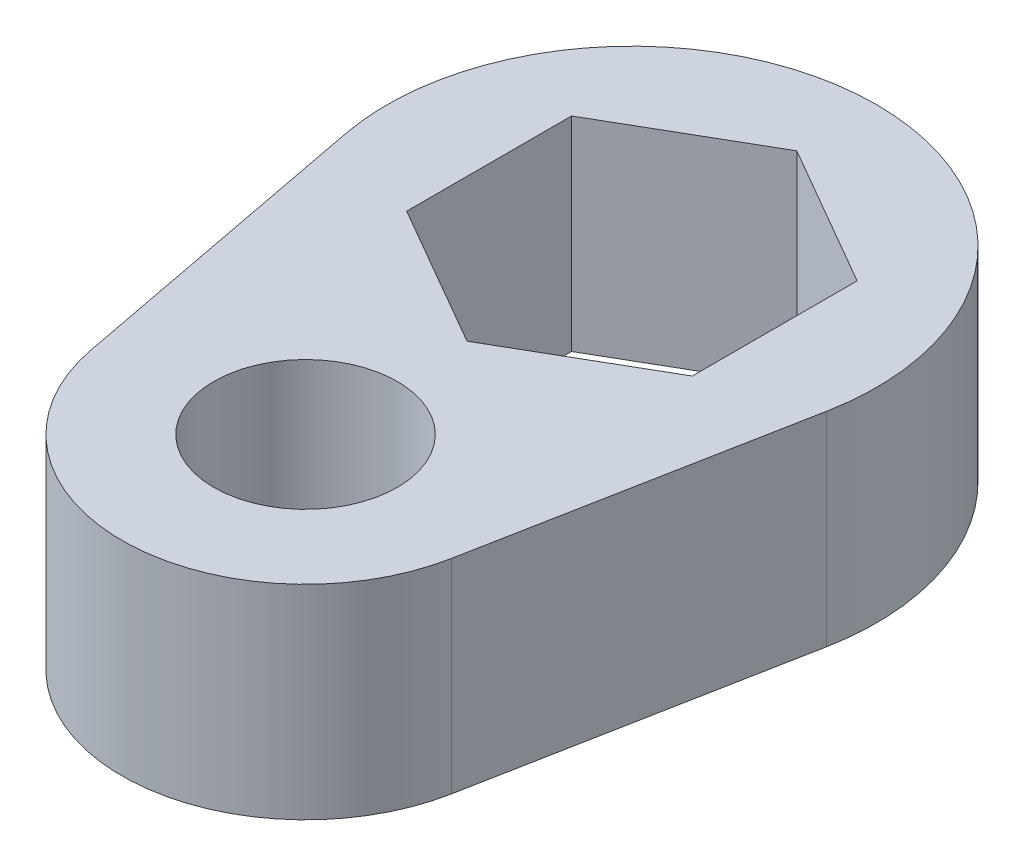
SolidWorks part; units mm, degrees
material "Printed PLA"
ref_plane "Front Plane" through (0, 0, 0) normal (0, 0, 1) x (1, 0, 0)
ref_plane "Top Plane" through (0, 0, 0) normal (0, 1, 0) x (1, 0, 0)
ref_plane "Right Plane" through (0, 0, 0) normal (1, 0, 0) x (0, 0, -1)
sketch "Sketch1" plane through (0, 0, 0) normal (0, 1, 0) x (1, 0, 0)
  line L0 (0, -8) -> (0, 0) construction
  line L1 (0, 4.0415) -> (-3.5, 2.0207)
  line L2 (-3.5, 2.0207) -> (-3.5, -2.0207)
  line L3 (-3.5, -2.0207) -> (0, -4.0415)
  line L4 (0, -4.0415) -> (3.5, -2.0207)
  line L5 (3.5, -2.0207) -> (3.5, 2.0207)
  line L6 (3.5, 2.0207) -> (0, 4.0415)
  line L7 (-5.8936, -1.125) -> (-4.4202, -8.8438)
  line L8 (5.8936, -1.125) -> (4.4202, -8.8438)
  circle A0 centre (0, 0) radius 3.5 construction
  circle A1 centre (0, -8) radius 2.25
  arc A2 (-4.4202, -8.8438) -> (4.4202, -8.8438) centre (0, -8) ccw
  arc A3 (5.8936, -1.125) -> (-5.8936, -1.125) centre (0, 0) ccw
  dimension "D3" = 4.5
  dimension "D4" = 6
  dimension "D5" = 4.5
  dimension "D1" = 8
  dimension "D2" = 7
extrude "Boss-Extrude1" add sketch "Sketch1" along normal blind 5
